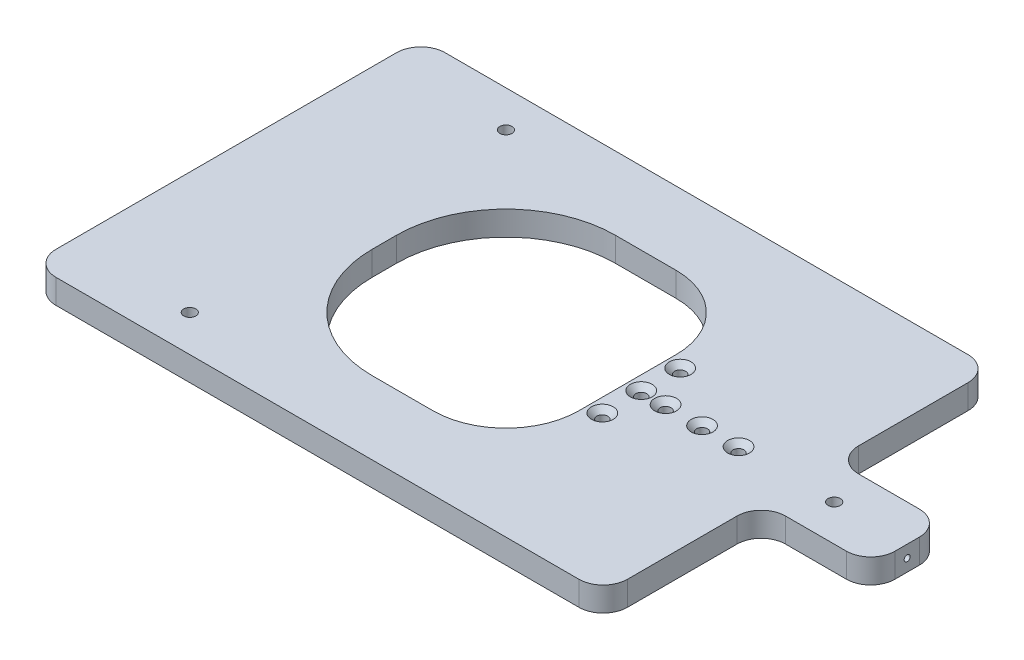
SolidWorks part; units mm, degrees
material "6061-T6 (SS)"
ref_plane "Front Plane" through (0, 0, 0) normal (0, 0, 1) x (1, 0, 0)
ref_plane "Top Plane" through (0, 0, 0) normal (0, 1, 0) x (1, 0, 0)
ref_plane "Right Plane" through (0, 0, 0) normal (1, 0, 0) x (0, 0, -1)
sketch "Sketch1" plane through (0, 0, 0) normal (0, 1, 0) x (1, 0, 0)
  line L0 (0, 0) -> (26.4502, 0) construction
  line L1 (0, 0) -> (0, 32.6737) construction
  line L2 (0, 0) -> (0, 160)
  line L3 (0, 160) -> (235, 160)
  line L5 (235, 160) -> (235, 95)
  line L6 (65, 130) -> (165, 130)
  line L7 (65, 130) -> (65, 30)
  line L8 (65, 30) -> (165, 30)
  line L9 (165, 130) -> (165, 30)
  line L10 (235, 95) -> (280, 95)
  line L11 (280, 95) -> (280, 65)
  line L12 (280, 65) -> (235, 65)
  line L13 (235, 65) -> (235, 0)
  line L14 (235, 0) -> (0, 0)
  line L17 (165, 80) -> (367.3241, 80) construction
  line L18 (50, 15) -> (50, 145) construction
  line L19 (180, 90.1906) -> (180, 72.0942) construction
  line L20 (195, 90.1906) -> (195, 72.0942) construction
  line L21 (210, 90.1906) -> (210, 72.0942) construction
  line L22 (180, 90.1906) -> (195, 90.1906) construction
  line L23 (195, 90.1906) -> (210, 90.1906) construction
  line L24 (210, 90.1906) -> (210, 72.0942) construction
  line L25 (210, 72.0942) -> (195, 72.0942) construction
  line L26 (195, 72.0942) -> (180, 72.0942) construction
  line L27 (165, 130) -> (65, 30) construction
  line L28 (65, 130) -> (165, 30) construction
  circle A0 centre (50, 145) radius 1.5
  circle A1 centre (50, 15) radius 1.5
  circle A2 centre (250, 80) radius 1.5
  circle A3 centre (180, 80) radius 4.7912 construction
  circle A4 centre (195, 80) radius 6.0976 construction
  circle A5 centre (280, 80) radius 4.5986 construction
  dimension "D13" = 3
  dimension "D14" = 3
  dimension "D15" = 3
  dimension "D19" = 30
  dimension "D2" = 160
  dimension "D3" = 45
  dimension "D4" = 100
  dimension "D5" = 100
  dimension "D6" = 30
  dimension "D7" = 65
  dimension "D8" = 30
  dimension "D9" = 65
  dimension "D10" = 185
  dimension "D11" = 15
  dimension "D12" = 15
  dimension "D16" = 15
  dimension "D17" = 15
  dimension "D18" = 15
  dimension "D20" = 170
extrude "Boss-Extrude1" add sketch "Sketch1" along normal blind 10
fillet "Fillet1" radius 10 8 edges at (235, 5, -95) (235, 5, -160) (0, 5, -160) (0, 5, 0) (235, 5, 0) (235, 5, -65) (280, 5, -95) (280, 5, -65)
sketch "Sketch8" plane through (0, 10, 0) normal (0, 1, 0) x (1, 0, 0)
  line L0 (165, 80) -> (318.5992, 80) construction
  line L1 (165, 30) -> (165, 130) construction
  line L2 (180.65, 89.8095) -> (180.65, 70.1905) construction
  line L3 (195.65, 89.8095) -> (195.65, 70.1905) construction
  line L4 (210.65, 89.8095) -> (210.65, 70.1905) construction
  line L5 (235, 105) -> (235, 150) construction
  circle A0 centre (180.65, 80) radius 6.647 construction
  circle A1 centre (195.65, 80) radius 7.1217 construction
  circle A2 centre (210.65, 80) radius 8.9204 construction
  dimension "D1" = 24.35
  dimension "D2" = 15
  dimension "D3" = 15
sketch "Sketch11" plane through (0, 10, 0) normal (0, 1, 0) x (1, 0, 0)
  line L0 (170.65, 148.3329) -> (170.65, 64) construction
  line L1 (165, 80) -> (318.5992, 80) construction
  line L3 (235, 105) -> (235, 150) construction
  circle A0 centre (170.65, 96) radius 6.2049
  circle A1 centre (170.65, 80) radius 11.7024
  circle A2 centre (170.65, 64) radius 10.527
  dimension "D1" = 16
  dimension "D2" = 16
  dimension "D4" = 64.35
hole_wizard "CSK for M4 Hex Socket Countersunk Cap Screw1" positions "Sketch12" profile "Sketch13" countersink size "M4" standard "ISO" end condition through all
sketch "Sketch12" plane through (0, 10, 0) normal (0, 1, 0) x (1, 0, 0)
  point P0 (170.65, 80)
  point P3 (180.65, 80)
  point P6 (195.65, 80)
  point P9 (210.65, 80)
  point P12 (170.65, 96)
  point P15 (170.65, 64)
sketch "Sketch13" plane through (170.65, 10, -80) normal (1, 0, 0) x (0, 0, 1)
  line L0 (0, 0) -> (0, 10)
  line L1 (0, 10) -> (2.25, 10)
  line L2 (2.25, 10) -> (2.25, 2.23)
  line L3 (2.25, 2.23) -> (4.48, 0)
  line L5 (4.48, 0) -> (0, 0)
  line L6 (-2.25, 2.23) -> (-4.48, 0) construction
  line L11 (0, -6.35) -> (0, 107.95) construction
  dimension "Thru Hole Dia." = 4.5
  dimension "Thru Hole Depth" = 10
  dimension "Near C'Sink Dia." = 8.96
  dimension "Near C'Sink Angle" = 90
sketch "Sketch14" plane through (0, 0, 0) normal (0, -1, 0) x (1, 0, 0)
  line L0 (50, -15) -> (15, -15) construction
  line L1 (165, -80) -> (65, -80) construction
  line L2 (65, -130) -> (65, -30) construction
  line L3 (170.65, -64) -> (215.1613, -64) construction
  line L4 (165, -80) -> (318.5992, -80) construction
  line L6 (280, -75) -> (280, -85) construction
  line L7 (0, -150) -> (0, -10) construction
  line L9 (10, 0) -> (225, 0) construction
  line L11 (225, -160) -> (10, -160) construction
  circle A3 centre (270, -80) radius 2.5
  circle A4 centre (15, -15) radius 2.5
  circle A5 centre (15, -140) radius 2.5
  dimension "D2" = 5
  dimension "D3" = 15
  dimension "D5" = 5
  dimension "D6" = 5
  dimension "D1" = 15
  dimension "D4" = 10
  dimension "D7" = 20
  dimension "D8" = 15
extrude "Cut-Extrude1" cut sketch "Sketch14" against normal blind 8
sketch "Sketch22" plane through (235, 0, 0) normal (1, 0, 0) x (0, 0, -1)
  line L0 (66.25, 7.77) -> (61.75, 3.885) construction
  line L2 (61.75, 7.77) -> (61.75, 0) construction
  line L3 (61.75, 7.77) -> (66.25, 3.885) construction
  line L4 (66.25, 0) -> (66.25, 7.77) construction
fillet "Fillet2" radius 45 2 edges at (65, 5, -30) (65, 5, -130)
hole_wizard "M6 Tapped Hole1" positions "Sketch25" profile "Sketch26" tap size "M6" standard "ISO" end condition through all
sketch "Sketch25" plane through (0, 10, 0) normal (0, 1, 0) x (1, 0, 0)
  point P0 (50, 145)
  point P12 (250, 80)
  point P15 (50, 15)
sketch "Sketch26" plane through (50, 10, -145) normal (1, 0, 0) x (0, 0, 1)
  line L0 (0, 0) -> (0, 10)
  line L1 (0, 10) -> (2.5, 10)
  line L2 (2.5, 10) -> (2.5, 0)
  line L5 (2.5, 0) -> (0, 0)
  line L11 (0, -6.35) -> (0, 107.95) construction
  dimension "Thru Tap Drill Dia." = 5
  dimension "Thru Tap Drill Depth" = 10
cosmetic thread "Hole Thread10" parameters "D1"=12, "D2"=6
cosmetic thread "Hole Thread11" parameters "D1"=12, "D2"=6
cosmetic thread "Hole Thread12" parameters "D1"=12, "D2"=6
sketch "Sketch27" plane through (280, 0, 0) normal (1, 0, 0) x (0, 0, -1)
  line L0 (80, 10) -> (80, 0) construction
  line L1 (86.647, 10) -> (73.353, 10) construction
  line L2 (75, 0) -> (85, 0) construction
  circle A0 centre (80, 5) radius 1.9781
hole_wizard "M3 Tapped Hole2" positions "3DSketch1" profile "Sketch29" tap size "M3" standard "ISO"
sketch3d "3DSketch1"
  point P0 (280, 5, -80)
sketch "Sketch29" plane through (280, 5, -80) normal (0, 1, 0) x (0, 0, -1)
  line L0 (0, 0) -> (0, 22.2511)
  line L1 (0, 22.2511) -> (1.25, 21.5)
  line L2 (1.25, 21.5) -> (1.25, 0)
  line L5 (1.25, 0) -> (0, 0)
  line L10 (0, 22.2511) -> (-1.25, 21.5) construction
  line L11 (0, -6.35) -> (0, 107.95) construction
  dimension "Tap Drill Dia." = 2.5
  dimension "Tap Drill Depth" = 21.5
  dimension "Drill Angle" = 118
cosmetic thread "Hole Thread4" parameters "D1"=15, "D2"=3
sketch "Sketch30" plane through (0, 0, 0) normal (-1, 0, 0) x (0, 0, 1)
  line L0 (-15, 8) -> (-15, 0) construction
  line L2 (-150, 0) -> (-10, 0) construction
  line L3 (-140, 8) -> (-140, 0) construction
  line L5 (-148.3329, 10) -> (-64, 10) construction
  line L7 (-150, 10) -> (-10, 10) construction
  line L8 (-17.5, 8) -> (-12.5, 8) construction
  line L9 (-142.5, 8) -> (-137.5, 8) construction
  circle A0 centre (-140, 5) radius 1.1285
  circle A2 centre (-15, 5) radius 0.9345
  dimension "D2" = 5
  dimension "D1" = 5
hole_wizard "M3 Tapped Hole1" positions "Sketch31" profile "Sketch32" tap size "M3" standard "ISO"
sketch "Sketch31" plane through (0, 0, 0) normal (-1, 0, 0) x (0, 0, 1)
  point P0 (-140, 5)
  point P3 (-15, 5)
cosmetic thread "Hole Thread5" parameters "D1"=20, "D2"=3
cosmetic thread "Hole Thread6" parameters "D1"=20, "D2"=3
sketch "Sketch32" plane through (0, 5, -140) normal (0, 1, 0) x (0, 0, 1)
  line L0 (0, 0) -> (0, 22.2511)
  line L1 (0, 22.2511) -> (1.25, 21.5)
  line L2 (1.25, 21.5) -> (1.25, 0)
  line L5 (1.25, 0) -> (0, 0)
  line L10 (0, 22.2511) -> (-1.25, 21.5) construction
  line L11 (0, -6.35) -> (0, 107.95) construction
  dimension "Tap Drill Dia." = 2.5
  dimension "Tap Drill Depth" = 21.5
  dimension "Drill Angle" = 118
fillet "Fillet3" radius 30 2 edges at (165, 5, -30) (165, 5, -130)
